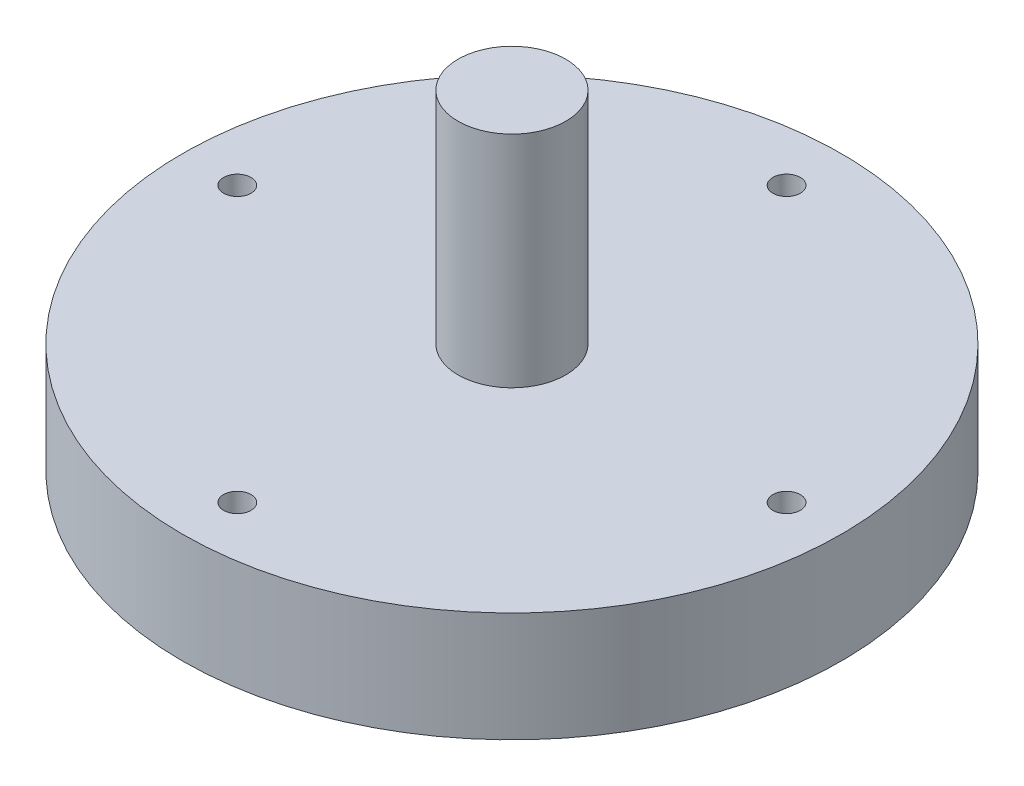
SolidWorks part; units mm, degrees
ref_plane "Front Plane" through (0, 0, 0) normal (0, 0, 1) x (1, 0, 0)
ref_plane "Top Plane" through (0, 0, 0) normal (0, 1, 0) x (1, 0, 0)
ref_plane "Right Plane" through (0, 0, 0) normal (1, 0, 0) x (0, 0, -1)
sketch "Sketch1" plane through (0, 0, 0) normal (0, 1, 0) x (1, 0, 0)
  circle A0 centre (0, 0) radius 38.1
  dimension "D1" = 76.2
extrude "Boss-Extrude1" add sketch "Sketch1" along normal blind 12.7
sketch "Sketch2" plane through (0, 12.7, 0) normal (0, 1, 0) x (1, 0, 0)
  circle A0 centre (0, 0) radius 6.223
  dimension "D1" = 12.446
extrude "Boss-Extrude2" add sketch "Sketch2" along normal blind 25.4
sketch "Sketch3" plane through (0, 12.7, 0) normal (0, 1, 0) x (1, 0, 0)
  line L0 (0, 31.75) -> (0, 0) construction
  circle A0 centre (0, 31.75) radius 1.5875
  dimension "D1" = 3.175
  dimension "D2" = 31.75
extrude "Cut-Extrude1" cut sketch "Sketch3" against normal through all
pattern_circular "CirPattern1" count 4 over 360 about axis through (0, 0, 0) along (0, 1, 0) of "Cut-Extrude1"
